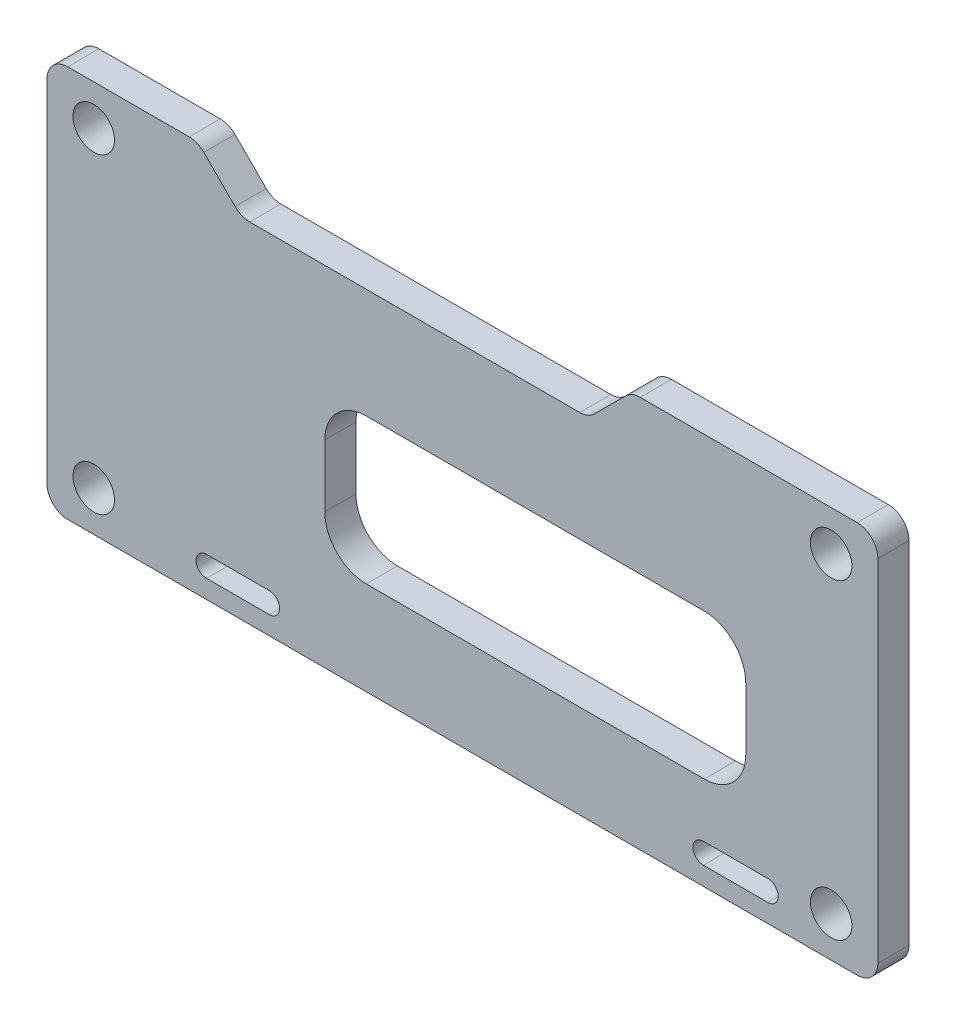
SolidWorks part; units mm, degrees
material "ABS"
ref_plane "前视基准面" through (0, 0, 0) normal (0, 0, 1) x (1, 0, 0)
ref_plane "上视基准面" through (0, 0, 0) normal (0, 1, 0) x (1, 0, 0)
ref_plane "右视基准面" through (0, 0, 0) normal (1, 0, 0) x (0, 0, -1)
sketch "草图1" plane through (0, 0, 0) normal (0, 0, 1) x (1, 0, 0)
  line L1 (-21.7384, 9.901) -> (13.7616, 9.901) construction
  line L2 (-21.7384, 9.901) -> (-21.7384, -5.099) construction
  line L3 (-21.7384, -5.099) -> (13.7616, -5.099) construction
  line L4 (13.7616, 9.901) -> (13.7616, -5.099) construction
  line L5 (-21.7384, 9.901) -> (13.7616, -5.099) construction
  line L6 (-21.7384, -5.099) -> (13.7616, 9.901) construction
  line L7 (-23.9884, 11.8368) -> (16.0116, 11.8368)
  line L8 (-23.9884, 11.8368) -> (-23.9884, -7.0348)
  line L9 (-23.9884, -7.0348) -> (16.0116, -7.0348)
  line L10 (16.0116, 11.8368) -> (16.0116, -7.0348)
  line L11 (-23.9884, 11.8368) -> (16.0116, -7.0348) construction
  line L12 (-23.9884, -7.0348) -> (16.0116, 11.8368) construction
  circle A0 centre (-21.7384, 9.901) radius 1
  circle A1 centre (-21.7384, -5.099) radius 1
  circle A2 centre (13.7616, -5.099) radius 1
  circle A3 centre (13.7616, 9.901) radius 1
  point P0 (-3.9884, 2.401)
  point P9 (-3.9884, 2.401)
  dimension "D3" = 40
  dimension "D1" = 15
  dimension "D2" = 35.5
extrude "凸台-拉伸1" add sketch "草图1" along normal blind 1.5
sketch "草图2" plane through (0, 0, 1.5) normal (0, 0, 1) x (1, 0, 0)
  line L0 (-16.7286, 11.8368) -> (-14.6398, 9.748)
  line L1 (16.0116, 11.8368) -> (-23.9884, 11.8368) construction
  line L2 (-14.6398, 9.748) -> (2.0715, 9.748)
  line L3 (2.0715, 9.748) -> (5.5197, 13.1963)
  line L4 (5.5197, 13.1963) -> (-14.8719, 13.1963)
  line L5 (-14.8719, 13.1963) -> (-16.7286, 11.8368)
  line L6 (-16.3104, -5.6502) -> (-13.2888, -5.6502) construction
  line L7 (-10.6138, 4.4657) -> (9.6518, 4.4657)
  line L8 (-10.6138, 4.4657) -> (-10.6138, -2.5364)
  line L9 (-10.6138, -2.5364) -> (9.6518, -2.5364)
  line L10 (9.6518, 4.4657) -> (9.6518, -2.5364)
  line L11 (-10.6138, 4.4657) -> (9.6518, -2.5364) construction
  line L12 (-10.6138, -2.5364) -> (9.6518, 4.4657) construction
  line L13 (-16.3104, -5.1502) -> (-13.2888, -5.1502)
  line L14 (-16.3104, -6.1502) -> (-13.2888, -6.1502)
  line L15 (7.6104, -5.6502) -> (10.7136, -5.6502) construction
  line L16 (7.6104, -5.1502) -> (10.7136, -5.1502)
  line L17 (7.6104, -6.1502) -> (10.7136, -6.1502)
  arc A0 (-16.3104, -5.1502) -> (-16.3104, -6.1502) centre (-16.3104, -5.6502) ccw
  arc A1 (-13.2888, -6.1502) -> (-13.2888, -5.1502) centre (-13.2888, -5.6502) ccw
  arc A2 (7.6104, -5.1502) -> (7.6104, -6.1502) centre (7.6104, -5.6502) ccw
  arc A3 (10.7136, -6.1502) -> (10.7136, -5.1502) centre (10.7136, -5.6502) ccw
  point P8 (-0.481, 0.9647)
  point P15 (-14.7996, -5.6502)
  point P20 (9.162, -5.6502)
  dimension "D1" = 0.5
  dimension "D2" = 0.5
  dimension "D3" = 45
  dimension "D4" = 45
extrude "切除-拉伸1" cut sketch "草图2" against normal blind 1.5
fillet "圆角1" radius 1 4 edges at (4.1603, 11.8368, 0.75) (2.0715, 9.748, 0.75) (-14.6398, 9.748, 0.75) (-16.7286, 11.8368, 0.75)
fillet "圆角2" radius 1 4 edges at (16.0116, 11.8368, 0.75) (16.0116, -7.0348, 0.75) (-23.9884, -7.0348, 0.75) (-23.9884, 11.8368, 0.75)
fillet "圆角3" radius 2 4 edges at (9.6518, 4.4657, 0.75) (9.6518, -2.5364, 0.75) (-10.6138, -2.5364, 0.75) (-10.6138, 4.4657, 0.75)
